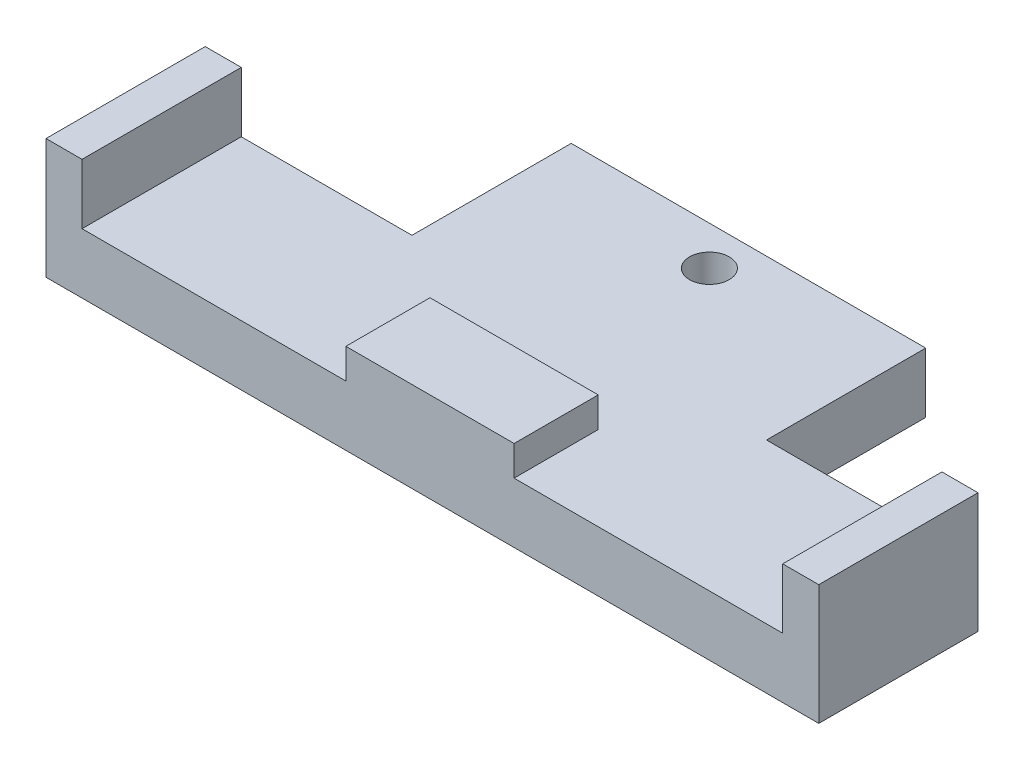
SolidWorks part; units mm, degrees
ref_plane "Front Plane" through (0, 0, 0) normal (0, 0, 1) x (1, 0, 0)
ref_plane "Top Plane" through (0, 0, 0) normal (0, 1, 0) x (1, 0, 0)
ref_plane "Right Plane" through (0, 0, 0) normal (1, 0, 0) x (0, 0, -1)
sketch "Sketch1" plane through (0, 0, 0) normal (0, 1, 0) x (1, 0, 0)
  line L0 (0, 3.25) -> (0, -3.25) construction
  line L1 (-14.75, 3.25) -> (14.75, 3.25)
  line L2 (-14.75, 3.25) -> (-14.75, -3.25)
  line L3 (-14.75, -3.25) -> (14.75, -3.25)
  line L4 (14.75, 3.25) -> (14.75, -3.25)
  line L5 (-14.75, 3.25) -> (14.75, -3.25) construction
  line L6 (-14.75, -3.25) -> (14.75, 3.25) construction
  line L7 (-14.75, -3.25) -> (14.75, -3.25)
  line L8 (-14.75, -3.25) -> (-14.75, -23.25)
  line L9 (-14.75, -23.25) -> (14.75, -23.25)
  line L10 (14.75, -3.25) -> (14.75, -23.25)
  circle A1 centre (0, 0) radius 1.65
  point P0 (0, 0)
  dimension "D4" = 3.3
  dimension "D1" = 6.5
  dimension "D2" = 29.5
  dimension "D3" = 20
extrude "Boss-Extrude1" add sketch "Sketch1" along normal blind 5 contours L10 L3 L8 L9 | L4 L1 L2 L3
sketch "Sketch3" plane through (0, 5, 0) normal (0, 1, 0) x (1, 0, 0)
  line L0 (14.75, 3.25) -> (14.75, -23.25) construction
  line L1 (14.75, -10) -> (29.35, -10)
  line L2 (14.75, -10) -> (14.75, -23.25)
  line L3 (14.75, -23.25) -> (29.35, -23.25)
  line L4 (29.35, -10) -> (29.35, -23.25)
  line L5 (-14.75, 3.25) -> (-14.75, -23.25) construction
  line L6 (-14.75, -10) -> (-28.95, -10)
  line L7 (-14.75, -10) -> (-14.75, -23.25)
  line L8 (-14.75, -23.25) -> (-28.95, -23.25)
  line L9 (-28.95, -10) -> (-28.95, -23.25)
  dimension "D1" = 14.6
  dimension "D2" = 14.2
extrude "Boss-Extrude2" add sketch "Sketch3" against normal blind 5
sketch "Sketch5" plane through (0, 5, 0) normal (0, 1, 0) x (1, 0, 0)
  line L1 (-28.95, -10) -> (-31.95, -10)
  line L2 (-28.95, -10) -> (-28.95, -23.25)
  line L3 (-28.95, -23.25) -> (-31.95, -23.25)
  line L4 (-31.95, -10) -> (-31.95, -23.25)
  line L5 (29.35, -10) -> (32.35, -10)
  line L6 (29.35, -10) -> (29.35, -23.25)
  line L7 (29.35, -23.25) -> (32.35, -23.25)
  line L8 (32.35, -10) -> (32.35, -23.25)
  dimension "D1" = 3
  dimension "D2" = 3
extrude "Boss-Extrude4" add sketch "Sketch5" along normal mid plane 10
sketch "Sketch6" plane through (0, 5, 0) normal (0, 1, 0) x (1, 0, 0)
  line L0 (0, 3.25) -> (0, -23.25) construction
  line L1 (-14.75, 3.25) -> (14.75, 3.25) construction
  line L2 (-28.95, -23.25) -> (29.35, -23.25) construction
  line L3 (0, -23.25) -> (7, -23.25)
  line L4 (7, -23.25) -> (7, -16.25)
  line L5 (7, -16.25) -> (-7, -16.25)
  line L6 (-7, -16.25) -> (-7, -23.25)
  line L7 (-7, -23.25) -> (0, -23.25)
  dimension "D1" = 7
  dimension "D2" = 7
  dimension "D3" = 7
extrude "Boss-Extrude5" add sketch "Sketch6" along normal blind 2.5
